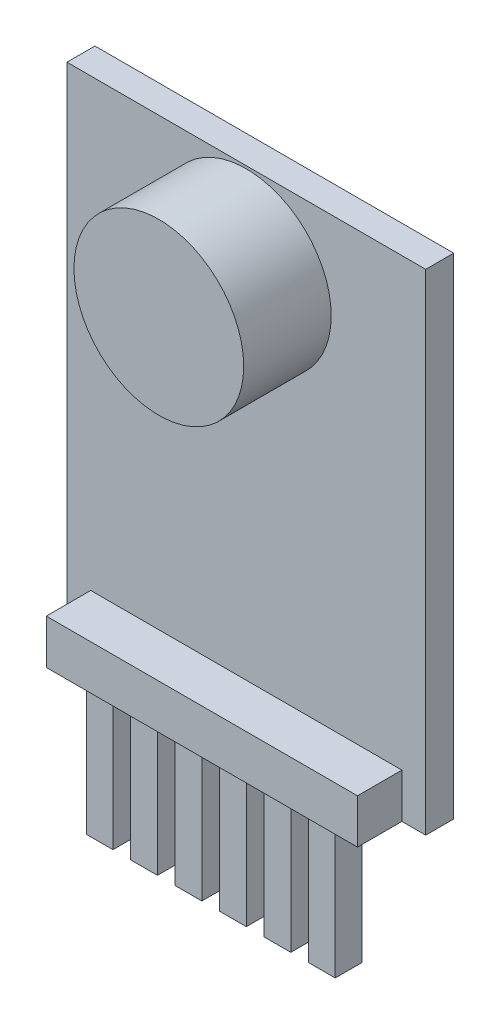
SolidWorks part; units mm, degrees
ref_plane "Front Plane" through (0, 0, 0) normal (0, 0, 1) x (1, 0, 0)
ref_plane "Top Plane" through (0, 0, 0) normal (0, 1, 0) x (1, 0, 0)
ref_plane "Right Plane" through (0, 0, 0) normal (1, 0, 0) x (0, 0, -1)
sketch "Sketch1" plane through (0, 0, 0) normal (0, 0, 1) x (1, 0, 0)
  line L1 (0, 0) -> (20.5, 0)
  line L2 (0, 0) -> (0, 28)
  line L3 (0, 28) -> (20.5, 28)
  line L4 (20.5, 0) -> (20.5, 28)
  dimension "D1" = 20.5
  dimension "D2" = 28
extrude "Boss-Extrude1" add sketch "Sketch1" along normal blind 1.6
sketch "Sketch2" plane through (0, 0, 1.6) normal (0, 0, 1) x (1, 0, 0)
  line L0 (0, 0) -> (20.5, 0) construction
  circle A0 centre (10.25, 23) radius 4.85
  point P4 (10.25, 0)
  dimension "D1" = 9.7
  dimension "D2" = 23
extrude "Boss-Extrude2" add sketch "Sketch2" along normal blind 5 separate body
sketch "Sketch3" plane through (0, 0, 1.6) normal (0, 0, 1) x (1, 0, 0)
  line L0 (0, 0) -> (20.5, 0) construction
  line L1 (1.36, 2.54) -> (19.14, 2.54)
  line L2 (1.36, 2.54) -> (1.36, 0)
  line L3 (1.36, 0) -> (19.14, 0)
  line L4 (19.14, 2.54) -> (19.14, 0)
  point P6 (10.25, 2.54)
  point P9 (10.25, 0)
  dimension "D1" = 17.78
  dimension "D2" = 2.54
extrude "Boss-Extrude3" add sketch "Sketch3" along normal blind 2.54 separate body
sketch "Sketch4" plane through (0, 0, 0) normal (0, -1, 0) x (1, 0, 0)
  line L0 (4.662, 2.87) -> (5.678, 2.87) construction
  line L1 (3.138, 3.632) -> (4.662, 3.632)
  line L2 (3.138, 3.632) -> (3.138, 2.108)
  line L3 (3.138, 2.108) -> (4.662, 2.108)
  line L4 (4.662, 3.632) -> (4.662, 2.108)
  line L5 (5.678, 3.632) -> (7.202, 3.632)
  line L6 (5.678, 3.632) -> (5.678, 2.108)
  line L7 (5.678, 2.108) -> (7.202, 2.108)
  line L8 (7.202, 3.632) -> (7.202, 2.108)
  line L9 (8.218, 3.632) -> (9.742, 3.632)
  line L10 (8.218, 3.632) -> (8.218, 2.108)
  line L11 (8.218, 2.108) -> (9.742, 2.108)
  line L12 (9.742, 3.632) -> (9.742, 2.108)
  line L13 (10.758, 3.632) -> (12.282, 3.632)
  line L14 (10.758, 3.632) -> (10.758, 2.108)
  line L15 (10.758, 2.108) -> (12.282, 2.108)
  line L16 (12.282, 3.632) -> (12.282, 2.108)
  line L17 (13.298, 3.632) -> (14.822, 3.632)
  line L18 (13.298, 3.632) -> (13.298, 2.108)
  line L19 (13.298, 2.108) -> (14.822, 2.108)
  line L20 (14.822, 3.632) -> (14.822, 2.108)
  line L21 (7.202, 2.87) -> (8.218, 2.87) construction
  line L22 (9.742, 2.87) -> (10.758, 2.87) construction
  line L23 (12.282, 2.87) -> (13.298, 2.87) construction
  line L24 (15.838, 3.632) -> (17.362, 3.632)
  line L25 (15.838, 3.632) -> (15.838, 2.108)
  line L26 (15.838, 2.108) -> (17.362, 2.108)
  line L27 (17.362, 3.632) -> (17.362, 2.108)
  line L28 (14.822, 2.87) -> (15.838, 2.87) construction
  line L29 (19.14, 4.14) -> (19.14, 1.6) construction
  line L30 (17.362, 2.4317) -> (19.14, 2.4317) construction
  line L31 (3.138, 2.4317) -> (1.36, 2.4317) construction
  line L32 (1.36, 4.14) -> (1.36, 1.6) construction
  point P34 (14.822, 2.87)
  point P35 (19.14, 2.87)
  dimension "D1" = 1.524
  dimension "D2" = 1.016
  dimension "D3" = 1.524
extrude "Boss-Extrude4" add sketch "Sketch4" along normal blind 7.62 separate body
